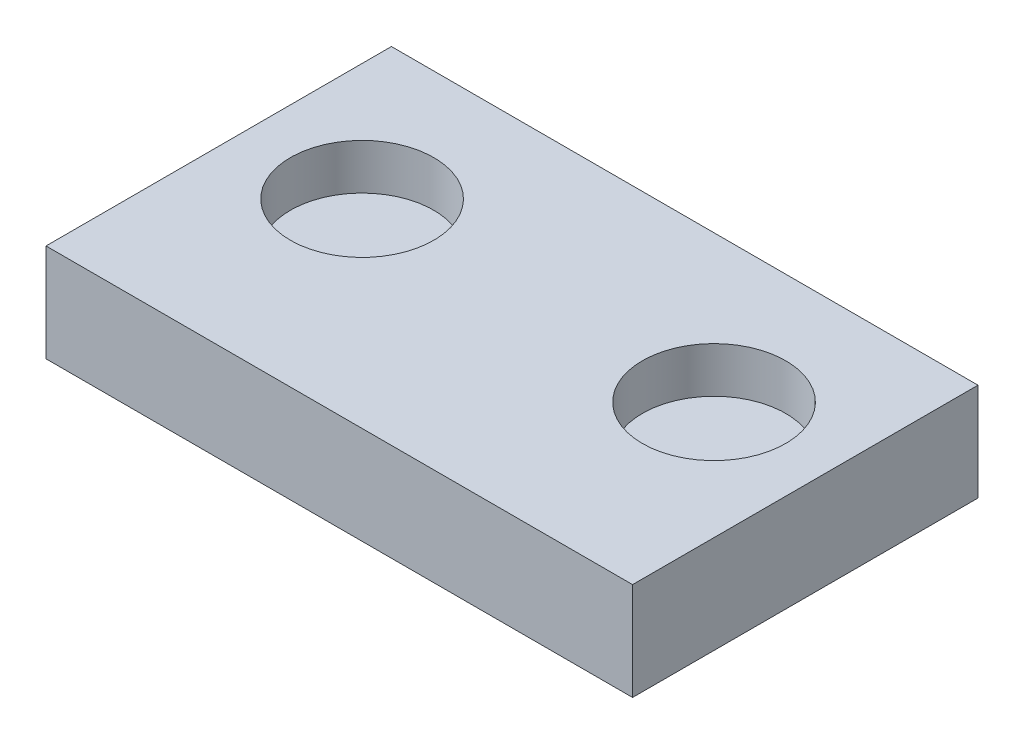
SolidWorks part; units mm, degrees
ref_plane "Alzado" through (0, 0, 0) normal (0, 0, 1) x (1, 0, 0)
ref_plane "Planta" through (0, 0, 0) normal (0, 1, 0) x (1, 0, 0)
ref_plane "Vista lateral" through (0, 0, 0) normal (1, 0, 0) x (0, 0, -1)
sketch "Croquis1" plane through (0, 0, 0) normal (0, 1, 0) x (1, 0, 0)
  line L1 (0, 0) -> (90, 0)
  line L2 (0, 0) -> (0, 53)
  line L3 (0, 53) -> (90, 53)
  line L4 (90, 0) -> (90, 53)
  dimension "D1" = 90
  dimension "D2" = 53
extrude "Saliente-Extruir1" add sketch "Croquis1" along normal blind 15 contours L2 L3 L4 L1
sketch "Croquis2" plane through (0, 15, 0) normal (0, 1, 0) x (1, 0, 0)
  line L0 (0, 0) -> (90, 0) construction
  line L1 (45, 53) -> (45, 0) construction
  line L2 (0, 53) -> (90, 53) construction
  line L3 (45, 30.5) -> (18, 30.5) construction
  line L5 (45, 30.5) -> (72, 30.5) construction
  circle A0 centre (18, 30.5) radius 11
  circle A1 centre (72, 30.5) radius 11
  dimension "D2" = 22
  dimension "D1" = 30.5
  dimension "D3" = 27
extrude "Cortar-Extruir1" cut sketch "Croquis2" against normal blind 7
